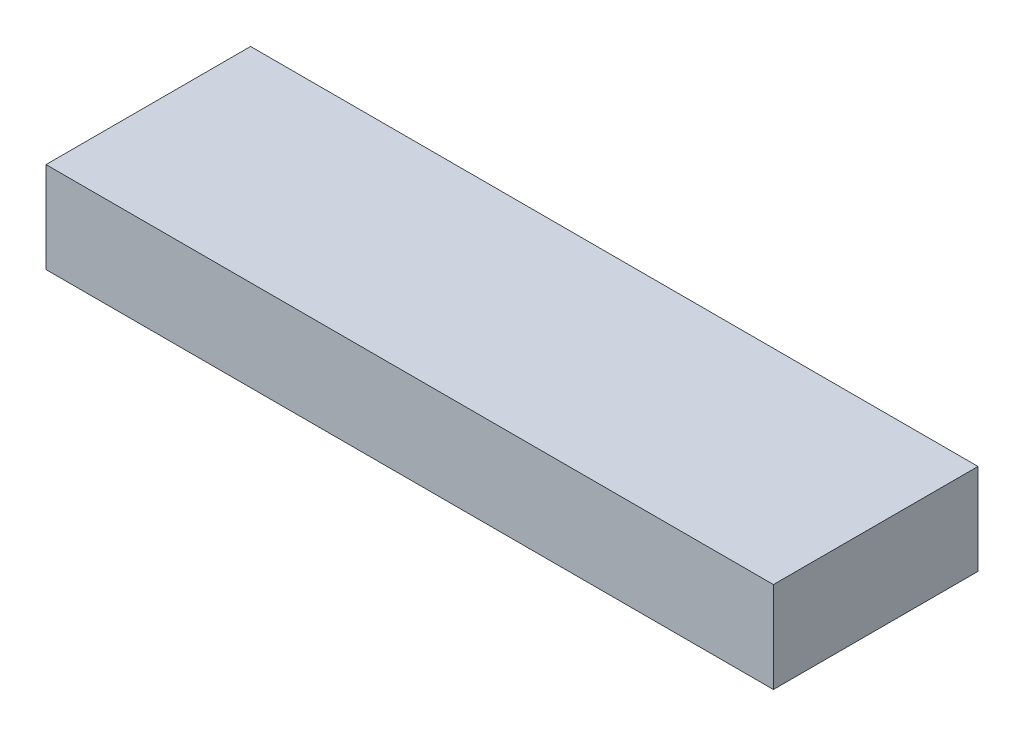
SolidWorks part; units mm, degrees
material "MDF"
ref_plane "Front Plane" through (0, 0, 0) normal (0, 0, 1) x (1, 0, 0)
ref_plane "Top Plane" through (0, 0, 0) normal (0, 1, 0) x (1, 0, 0)
ref_plane "Right Plane" through (0, 0, 0) normal (1, 0, 0) x (0, 0, -1)
sketch "Sketch1" plane through (0, 0, 0) normal (0, 0, 1) x (1, 0, 0)
  line L1 (-228.0888, -450.85) -> (-126.4888, -450.85)
  line L2 (-228.0888, -450.85) -> (-228.0888, -463.55)
  line L3 (-228.0888, -463.55) -> (-126.4888, -463.55)
  line L4 (-126.4888, -450.85) -> (-126.4888, -463.55)
  dimension "D1" = 12.7
  dimension "D2" = 101.6
extrude "Boss-Extrude1" add sketch "Sketch1" along normal blind 28.575 contours L1 L4 L3 L2
